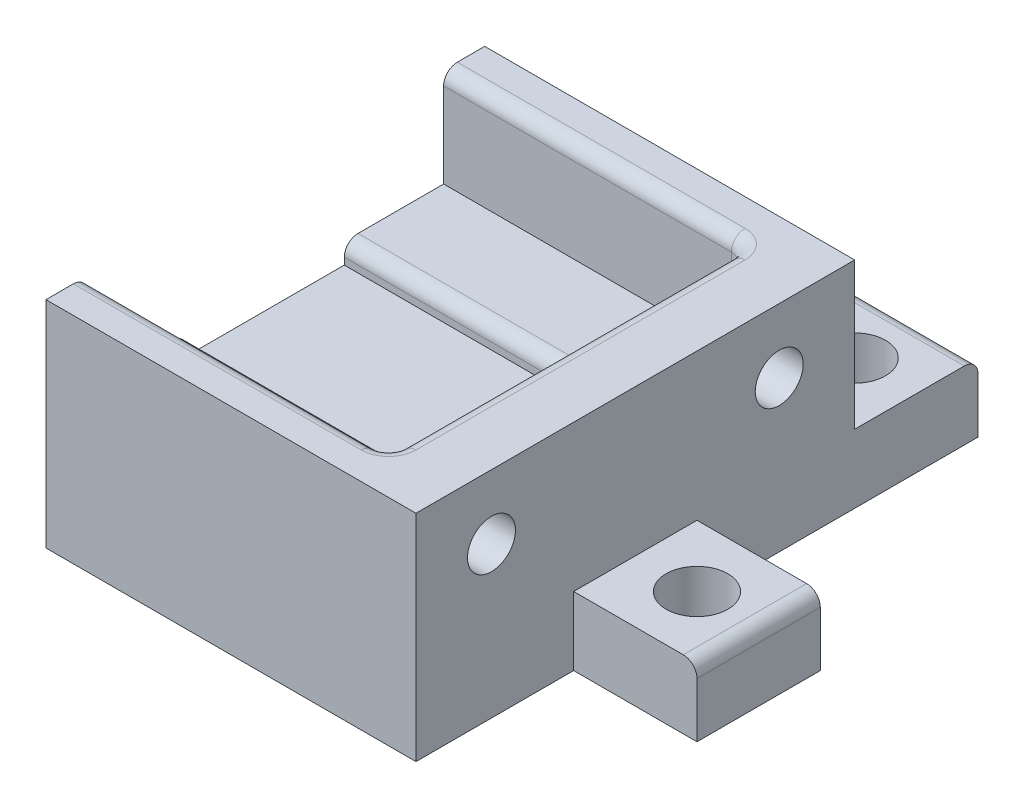
SolidWorks part; units mm, degrees
ref_plane "Front" through (0, 0, 0) normal (0, 0, 1) x (1, 0, 0)
ref_plane "Top" through (0, 0, 0) normal (0, 1, 0) x (1, 0, 0)
ref_plane "Right" through (0, 0, 0) normal (1, 0, 0) x (0, 0, -1)
sketch "Sketch1" plane through (0, 0, 0) normal (1, 0, 0) x (0, 0, -1)
  line L0 (-13.0089, 0) -> (13.0089, 0)
  line L1 (13.0089, 0) -> (13.0089, 8.5)
  line L2 (13.0089, 8.5) -> (5.7589, 8.5)
  line L3 (5.7589, 8.5) -> (5.7589, 7)
  line L4 (5.7589, 7) -> (-5.7589, 7)
  line L5 (-5.7589, 7) -> (-5.7589, 8.5)
  line L6 (-5.7589, 8.5) -> (-13.0089, 8.5)
  line L7 (-13.0089, 8.5) -> (-13.0089, 0)
  dimension "D1" = 8.5
  dimension "D2" = 7.25
  dimension "D3" = 26.0178
  dimension "D4" = 1.5
extrude "Boss-Extrude1" add sketch "Sketch1" along normal mid plane 22
sketch "Sketch3" plane through (0, 0, 0) normal (0, -1, 0) x (1, 0, 0)
  line L1 (-11, -13.0089) -> (11, -13.0089)
  line L2 (-11, -13.0089) -> (-11, -16.0089)
  line L3 (-11, -16.0089) -> (11, -16.0089)
  line L4 (11, -13.0089) -> (11, -16.0089)
  line L5 (-11, 13.0089) -> (11, 13.0089)
  line L6 (-11, 13.0089) -> (-11, 16.0089)
  line L7 (-11, 16.0089) -> (11, 16.0089)
  line L8 (11, 13.0089) -> (11, 16.0089)
  dimension "D1" = 3
  dimension "D2" = 22
  dimension "D3" = 3
  dimension "D4" = 22
extrude "Boss-Extrude2" add sketch "Sketch3" against normal blind 15.7
sketch "Sketch4" plane through (11, 0, 0) normal (1, 0, 0) x (0, 0, -1)
  line L0 (0, 0) -> (0, 15.7) construction
  line L1 (-16.0089, 0) -> (16.0089, 0) construction
  line L2 (-8.8, 15.7) -> (-16.0089, 15.7)
  line L3 (-16.0089, 15.7) -> (-16.0089, 0) construction
  line L4 (-16.0089, 15.7) -> (-16.0089, 0)
  line L5 (-16.0089, 0) -> (16.0089, 0)
  line L6 (16.0089, 0) -> (16.0089, 15.7)
  line L7 (16.0089, 15.7) -> (16.0089, 0) construction
  line L8 (16.0089, 15.7) -> (-8.8, 15.7)
  dimension "D2" = 15.7
extrude "Boss-Extrude3" add sketch "Sketch4" along normal blind 5
sketch "Sketch5" plane through (16, 0, 0) normal (1, 0, 0) x (0, 0, -1)
  line L0 (-16.0089, 11) -> (-10.5, 11) construction
  line L1 (-16.0089, 15.7) -> (-16.0089, 0) construction
  line L2 (-10.5, 11) -> (-10.5, 0) construction
  line L3 (-16.0089, 0) -> (16.0089, 0) construction
  line L4 (0, 0) -> (0, 15.7) construction
  line L5 (16.0089, 15.7) -> (-16.0089, 15.7) construction
  circle A0 centre (-10.5, 11) radius 1.75
  circle A1 centre (10.5, 11) radius 1.75
  dimension "D3" = 3.5
  dimension "D1" = 5.5089
  dimension "D2" = 11
extrude "Cut-Extrude1" cut sketch "Sketch5" against normal through all
sketch "Sketch6" plane through (0, 0, 0) normal (0, -1, 0) x (1, 0, 0)
  line L0 (16, 16.0089) -> (16, -16.0089) construction
  line L5 (0, 0) -> (16, 0) construction
  line L13 (16, 4.5) -> (25, 4.5)
  line L14 (-11, -16.0089) -> (16, -16.0089) construction
  line L15 (16, -25.0089) -> (7, -25.0089)
  line L20 (16, -25.0089) -> (16, -16.0089)
  line L21 (16, -16.0089) -> (7, -16.0089)
  line L22 (7, -25.0089) -> (7, -16.0089)
  line L23 (16, 4.5) -> (16, -4.5)
  line L24 (16, -4.5) -> (25, -4.5)
  line L25 (25, 4.5) -> (25, -4.5)
  dimension "D1" = 9
  dimension "D2" = 9
  dimension "D3" = 9
  dimension "D4" = 9
extrude "Boss-Extrude4" add sketch "Sketch6" against normal blind 5
sketch "Sketch7" plane through (0, 5, 0) normal (0, 1, 0) x (1, 0, 0)
  line L0 (25, 0) -> (16, 0) construction
  line L1 (7, 25.0089) -> (16, 25.0089) construction
  line L2 (16, 16.0089) -> (7, 16.0089) construction
  line L3 (20.5, 4.5) -> (20.5, -4.5) construction
  line L6 (11.5, 25.0089) -> (11.5, 16.0089) construction
  line L7 (16, -4.5) -> (16, 4.5) construction
  line L8 (25, 4.5) -> (25, -4.5) construction
  line L9 (7, 20.5089) -> (16, 20.5089) construction
  line L10 (16, 4.5) -> (25, 4.5) construction
  line L11 (25, -4.5) -> (16, -4.5) construction
  line L12 (7, 16.0089) -> (7, 25.0089) construction
  line L15 (16, 25.0089) -> (16, 16.0089) construction
  circle A0 centre (20.5, 0) radius 2.25
  circle A1 centre (11.5, 20.5089) radius 2.25
  point P5 (16, 0)
  point P11 (25, 0)
  point P29 (20.5, 4.5)
  dimension "D1" = 4.5
extrude "Cut-Extrude2" cut sketch "Sketch7" against normal through all
fillet "Fillet1" radius 1 9 edges at (0, 8.5, 5.7589) (0, 8.5, -5.7589) (25, 5, 0) (11.5, 5, -25.0089) (0, 15.7, 13.0089) (11, 15.7, 0) (0, 15.7, -13.0089) (11, 12.1, 13.0089) (11, 12.1, -13.0089)
